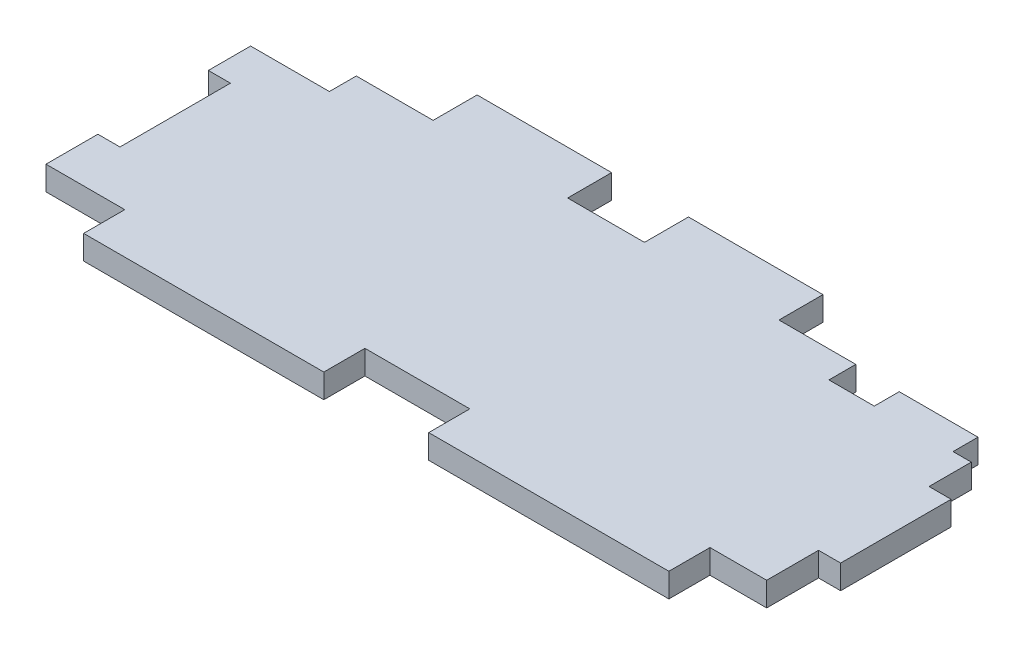
SolidWorks part; units mm, degrees
ref_plane "Front Plane" through (0, 0, 0) normal (0, 0, 1) x (1, 0, 0)
ref_plane "Top Plane" through (0, 0, 0) normal (0, 1, 0) x (1, 0, 0)
ref_plane "Right Plane" through (0, 0, 0) normal (1, 0, 0) x (0, 0, -1)
sketch "Sketch1" plane through (0, 0, 0) normal (0, 1, 0) x (1, 0, 0)
  line L0 (-49.022, -7.3025) -> (-49.022, 0)
  line L1 (46.2534, -7.3025) -> (46.2534, 0)
  line L2 (-49.022, 0) -> (-49.022, 7.3025)
  line L3 (-49.022, 7.3025) -> (-51.943, 7.3025)
  line L4 (-51.943, 7.3025) -> (-51.943, 14.1605)
  line L5 (-51.943, 14.1605) -> (-41.529, 14.1605)
  line L6 (-41.529, 14.1605) -> (-41.529, 17.0815)
  line L7 (-41.529, 17.0815) -> (-31.369, 17.0815)
  line L8 (-31.369, 17.0815) -> (-31.369, 22.5171)
  line L9 (-31.369, 22.5171) -> (-13.589, 22.5171)
  line L10 (-13.589, 22.5171) -> (-13.589, 17.0815)
  line L11 (-13.589, 17.0815) -> (-3.429, 17.0815)
  line L12 (-3.429, 17.0815) -> (-3.429, 22.5171)
  line L13 (-3.429, 22.5171) -> (14.351, 22.5171)
  line L14 (14.351, 22.5171) -> (14.351, 17.0815)
  line L15 (-1000, 0) -> (49000, 0) construction
  line L16 (0, -1000) -> (0, 49000) construction
  line L17 (35.8394, -19.5961) -> (35.8394, -14.1605)
  line L18 (4.0894, -14.1605) -> (4.0894, -19.5961)
  line L19 (43.3324, -7.3025) -> (46.2534, -7.3025)
  line L20 (43.3324, -14.1605) -> (43.3324, -7.3025)
  line L21 (35.8394, -14.1605) -> (43.3324, -14.1605)
  line L22 (4.0894, -19.5961) -> (35.8394, -19.5961)
  line L23 (-9.779, -14.1605) -> (4.0894, -14.1605)
  line L24 (-9.779, -19.5961) -> (-9.779, -14.1605)
  line L25 (-41.529, -19.5961) -> (-9.779, -19.5961)
  line L26 (-41.529, -14.1605) -> (-41.529, -19.5961)
  line L27 (-51.943, -14.1605) -> (-41.529, -14.1605)
  line L28 (-51.943, -7.3025) -> (-51.943, -14.1605)
  line L29 (-49.022, -7.3025) -> (-51.943, -7.3025)
  line L30 (14.351, 17.0815) -> (24.511, 17.0815)
  line L31 (24.511, 17.0815) -> (24.511, 13.9065)
  line L32 (24.511, 13.9065) -> (30.5054, 13.9065)
  line L33 (30.5054, 13.9065) -> (30.5054, 17.0815)
  line L34 (30.5054, 17.0815) -> (40.9194, 17.0815)
  line L35 (40.9194, 17.0815) -> (40.9194, 14.2621)
  line L36 (40.9194, 14.2621) -> (43.3324, 14.2621)
  line L37 (43.3324, 14.2621) -> (43.3324, 7.3025)
  line L38 (43.3324, 7.3025) -> (46.2534, 7.3025)
  line L39 (46.2534, 7.3025) -> (46.2534, 0)
  dimension "D1" = 7.3025
  dimension "D2" = 2.921
  dimension "D3" = 6.858
  dimension "D4" = 10.414
  dimension "D5" = 5.4356
  dimension "D6" = 31.75
  dimension "D8" = 13.8684
  dimension "D10" = 31.75
  dimension "D12" = 7.493
  dimension "D13" = 6.858
  dimension "D14" = 7.3025
  dimension "D16" = 51.943
  dimension "D17" = 2.921
  dimension "D18" = 7.3025
  dimension "D19" = 10.414
  dimension "D20" = 7.3025
  dimension "D21" = 2.921
  dimension "D22" = 6.858
  dimension "D23" = 10.414
  dimension "D24" = 2.921
  dimension "D25" = 10.16
  dimension "D26" = 5.4356
  dimension "D27" = 5.4356
  dimension "D28" = 5.4356
  dimension "D29" = 5.4356
  dimension "D30" = 17.78
  dimension "D31" = 17.78
  dimension "D32" = 10.16
  dimension "D33" = 10.16
  dimension "D34" = 3.175
  dimension "D35" = 5.9944
  dimension "D37" = 2.8194
  dimension "D38" = 2.413
extrude "Boss-Extrude2" add sketch "Sketch1" along normal mid plane 3.175
sketch "Sketch2" plane through (0, 1.5875, 0) normal (0, 1, 0) x (1, 0, 0)
  line L0 (-51.943, 14.1605) -> (-51.943, 7.3025) construction
  line L1 (-41.529, 14.1605) -> (-51.943, 14.1605)
  line L2 (-41.529, 14.1605) -> (-41.529, 12.8905)
  line L3 (-41.529, 12.8905) -> (-51.943, 12.8905)
  line L4 (-51.943, 14.1605) -> (-51.943, 12.8905)
  line L5 (43.3324, 7.3025) -> (43.3324, 14.2621) construction
  line L6 (30.5054, 13.9065) -> (24.511, 13.9065)
  line L7 (30.5054, 13.9065) -> (30.5054, 12.8905)
  line L8 (30.5054, 12.8905) -> (24.511, 12.8905)
  line L9 (24.511, 13.9065) -> (24.511, 12.8905)
  line L10 (40.9194, 14.2621) -> (43.3324, 14.2621)
  line L11 (40.9194, 14.2621) -> (40.9194, 12.8905)
  line L12 (40.9194, 12.8905) -> (43.3324, 12.8905)
  line L13 (43.3324, 14.2621) -> (43.3324, 12.8905)
  line L14 (24.511, 13.9065) -> (24.511, 17.0815) construction
  dimension "D1" = 1.27
extrude "Cut-Extrude1" cut sketch "Sketch2" against normal through all
sketch "Sketch3" plane through (0, 1.5875, 0) normal (0, 1, 0) x (1, 0, 0)
  line L0 (-41.529, 17.0815) -> (-41.529, 12.8905) construction
  line L1 (-31.369, 17.0815) -> (-41.529, 17.0815)
  line L2 (-31.369, 17.0815) -> (-31.369, 16.4465)
  line L3 (-31.369, 16.4465) -> (-41.529, 16.4465)
  line L4 (-41.529, 17.0815) -> (-41.529, 16.4465)
  line L5 (24.511, 12.8905) -> (24.511, 17.0815) construction
  line L6 (-13.589, 17.0815) -> (-3.429, 17.0815)
  line L7 (-13.589, 17.0815) -> (-13.589, 16.4465)
  line L8 (-13.589, 16.4465) -> (-3.429, 16.4465)
  line L9 (-3.429, 17.0815) -> (-3.429, 16.4465)
  line L10 (14.351, 17.0815) -> (24.511, 17.0815)
  line L11 (14.351, 17.0815) -> (14.351, 16.4465)
  line L12 (14.351, 16.4465) -> (24.511, 16.4465)
  line L13 (24.511, 17.0815) -> (24.511, 16.4465)
  line L14 (30.5054, 17.0815) -> (30.5054, 12.8905) construction
  line L15 (40.9194, 17.0815) -> (30.5054, 17.0815)
  line L16 (40.9194, 17.0815) -> (40.9194, 16.4465)
  line L17 (40.9194, 16.4465) -> (30.5054, 16.4465)
  line L18 (30.5054, 17.0815) -> (30.5054, 16.4465)
  line L19 (-3.429, 22.5171) -> (-3.429, 17.0815) construction
  dimension "D1" = 0.635
extrude "Cut-Extrude2" cut sketch "Sketch3" against normal through all
sketch "Sketch4" plane through (0, 1.5875, 0) normal (0, 1, 0) x (1, 0, 0)
  line L0 (-13.589, 16.4465) -> (-13.589, 22.5171) construction
  line L1 (-31.369, 22.5171) -> (-13.589, 22.5171)
  line L2 (-31.369, 22.5171) -> (-31.369, 22.2631)
  line L3 (-31.369, 22.2631) -> (-13.589, 22.2631)
  line L4 (-13.589, 22.5171) -> (-13.589, 22.2631)
  line L5 (14.351, 16.4465) -> (14.351, 22.5171) construction
  line L6 (-3.429, 22.5171) -> (14.351, 22.5171)
  line L7 (-3.429, 22.5171) -> (-3.429, 22.2631)
  line L8 (-3.429, 22.2631) -> (14.351, 22.2631)
  line L9 (14.351, 22.5171) -> (14.351, 22.2631)
  dimension "D1" = 0.254
extrude "Cut-Extrude3" cut sketch "Sketch4" against normal through all
sketch "Sketch5" plane through (0, 1.5875, 0) normal (0, 1, 0) x (1, 0, 0)
  line L0 (40.9194, 12.8905) -> (40.9194, 16.4465) construction
  line L1 (30.5054, 16.4465) -> (40.9194, 16.4465)
  line L2 (30.5054, 16.4465) -> (30.5054, 16.1925)
  line L3 (30.5054, 16.1925) -> (40.9194, 16.1925)
  line L4 (40.9194, 16.4465) -> (40.9194, 16.1925)
  dimension "D1" = 0.254
extrude "Cut-Extrude4" cut sketch "Sketch5" against normal through all
